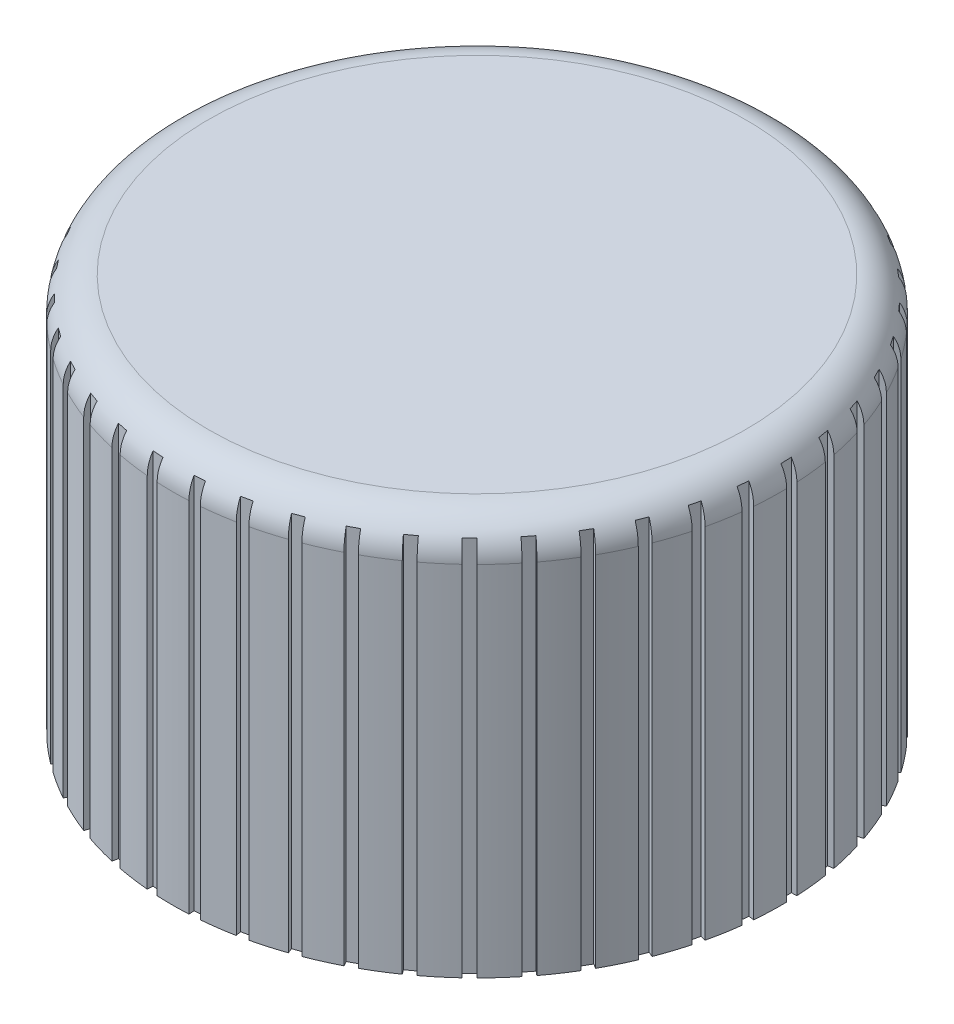
SolidWorks part; units mm, degrees
ref_plane "Front Plane" through (0, 0, 0) normal (0, 0, 1) x (1, 0, 0)
ref_plane "Top Plane" through (0, 0, 0) normal (0, 1, 0) x (1, 0, 0)
ref_plane "Right Plane" through (0, 0, 0) normal (1, 0, 0) x (0, 0, -1)
sketch "草图1" plane through (0, 0, 0) normal (0, 1, 0) x (1, 0, 0)
  circle A0 centre (0, 0) radius 8.5
extrude "凸台-拉伸1" add sketch "草图1" along normal blind 11
sketch "草图2" plane through (0, 0, 0) normal (0, -1, 0) x (1, 0, 0)
  circle A0 centre (0, 0) radius 2.95
extrude "切除-拉伸1" cut sketch "草图2" against normal blind 8.8
fillet "圆角1" radius 1 1 edges at (0, 11, 8.5)
sketch "草图3" plane through (0, 0, 0) normal (0, -1, 0) x (1, 0, 0)
  line L9 (4.7426, 1.5835) -> (6.5, 2.5981)
  line L10 (1, 4.899) -> (1, 6.9282)
  line L11 (-1, 4.899) -> (-1, 6.9282)
  line L12 (3.7426, 3.3155) -> (5.5, 4.3301)
  line L13 (3.7426, -3.3155) -> (5.5, -4.3301)
  line L14 (4.7426, -1.5835) -> (6.5, -2.5981)
  line L15 (-1, -4.899) -> (-1, -6.9282)
  line L16 (1, -4.899) -> (1, -6.9282)
  line L17 (-4.7426, -1.5835) -> (-6.5, -2.5981)
  line L18 (-3.7426, -3.3155) -> (-5.5, -4.3301)
  line L19 (-3.7426, 3.3155) -> (-5.5, 4.3301)
  line L20 (-4.7426, 1.5835) -> (-6.5, 2.5981)
  arc A0 (-4.7426, 1.5835) -> (-4.7426, -1.5835) centre (0, 0) ccw
  arc A11 (-6.5, 2.5981) -> (-6.5, -2.5981) centre (0, 0) ccw
  arc A12 (-3.7426, -3.3155) -> (-1, -4.899) centre (0, 0) ccw
  arc A13 (-5.5, -4.3301) -> (-1, -6.9282) centre (0, 0) ccw
  arc A14 (1, -4.899) -> (3.7426, -3.3155) centre (0, 0) ccw
  arc A15 (1, -6.9282) -> (5.5, -4.3301) centre (0, 0) ccw
  arc A16 (4.7426, -1.5835) -> (4.7426, 1.5835) centre (0, 0) ccw
  arc A17 (6.5, -2.5981) -> (6.5, 2.5981) centre (0, 0) ccw
  arc A18 (3.7426, 3.3155) -> (1, 4.899) centre (0, 0) ccw
  arc A19 (5.5, 4.3301) -> (1, 6.9282) centre (0, 0) ccw
  arc A20 (-1, 4.899) -> (-3.7426, 3.3155) centre (0, 0) ccw
  arc A21 (-1, 6.9282) -> (-5.5, 4.3301) centre (0, 0) ccw
  point P0 (1, 0)
  point P1 (0, 7)
  point P4 (1, 11.9)
  point P5 (-1, 0)
  point P8 (-1, 11.9)
  point P36 (0, 0)
  dimension "D1" = 6
extrude "切除-拉伸2" cut sketch "草图3" against normal blind 9
sketch "草图5" plane through (0, 11, 0) normal (0, 1, 0) x (1, 0, 0)
  line L2 (1.1615, 8.2645) -> (1.0132, 8.2854)
  line L3 (0, 8.3457) -> (-0.1498, 8.3457)
  line L4 (0, 8.3457) -> (0.1498, 8.3457)
  line L5 (-0.1498, 8.3457) -> (-0.1483, 8.4987)
  line L6 (0.1498, 8.3457) -> (0.1483, 8.4987)
  line L7 (1.1615, 8.2645) -> (1.3098, 8.2437)
  line L8 (1.0132, 8.2854) -> (1.0359, 8.4366)
  line L9 (1.3098, 8.2437) -> (1.3297, 8.3954)
  line L10 (2.3004, 8.0224) -> (2.1564, 8.0637)
  line L11 (2.3004, 8.0224) -> (2.4444, 7.9812)
  line L12 (2.1564, 8.0637) -> (2.2, 8.2104)
  line L13 (2.4444, 7.9812) -> (2.4852, 8.1286)
  line L14 (3.3945, 7.6242) -> (3.2577, 7.6851)
  line L15 (3.3945, 7.6242) -> (3.5313, 7.5633)
  line L16 (3.2577, 7.6851) -> (3.3212, 7.8243)
  line L17 (3.5313, 7.5633) -> (3.5923, 7.7036)
  line L18 (4.4226, 7.0776) -> (4.2956, 7.157)
  line L19 (4.4226, 7.0776) -> (4.5496, 6.9982)
  line L20 (4.2956, 7.157) -> (4.3778, 7.2859)
  line L21 (4.5496, 6.9982) -> (4.6294, 7.1287)
  line L22 (5.3645, 6.3932) -> (5.2498, 6.4895)
  line L23 (5.3645, 6.3932) -> (5.4793, 6.2969)
  line L24 (5.2498, 6.4895) -> (5.3492, 6.6057)
  line L25 (5.4793, 6.2969) -> (5.5765, 6.415)
  line L26 (6.2021, 5.5844) -> (6.1019, 5.6957)
  line L27 (6.2021, 5.5844) -> (6.3023, 5.4731)
  line L28 (6.1019, 5.6957) -> (6.2165, 5.797)
  line L29 (6.3023, 5.4731) -> (6.415, 5.5765)
  line L30 (6.9189, 4.6669) -> (6.8352, 4.791)
  line L31 (6.9189, 4.6669) -> (7.0027, 4.5427)
  line L32 (6.8352, 4.791) -> (6.9628, 4.8754)
  line L33 (7.0027, 4.5427) -> (7.1287, 4.6294)
  line L34 (7.5011, 3.6585) -> (7.4355, 3.7931)
  line L35 (7.5011, 3.6585) -> (7.5668, 3.5239)
  line L36 (7.4355, 3.7931) -> (7.5736, 3.8589)
  line L37 (7.5668, 3.5239) -> (7.7036, 3.5923)
  line L38 (7.9373, 2.579) -> (7.891, 2.7214)
  line L39 (7.9373, 2.579) -> (7.9836, 2.4365)
  line L40 (7.891, 2.7214) -> (8.0369, 2.7673)
  line L41 (7.9836, 2.4365) -> (8.1286, 2.4852)
  line L42 (8.219, 1.4492) -> (8.1929, 1.5967)
  line L43 (8.219, 1.4492) -> (8.245, 1.3017)
  line L44 (8.1929, 1.5967) -> (8.3438, 1.6219)
  line L45 (8.245, 1.3017) -> (8.3954, 1.3297)
  line L46 (8.3407, 0.2913) -> (8.3354, 0.4409)
  line L47 (8.3407, 0.2913) -> (8.3459, 0.1416)
  line L48 (8.3354, 0.4409) -> (8.4884, 0.4449)
  line L49 (8.3459, 0.1416) -> (8.4987, 0.1483)
  line L50 (8.3, -0.8724) -> (8.3157, -0.7234)
  line L51 (8.3, -0.8724) -> (8.2844, -1.0213)
  line L52 (8.3157, -0.7234) -> (8.4677, -0.7408)
  line L53 (8.2844, -1.0213) -> (8.4366, -1.0359)
  line L54 (8.0978, -2.019) -> (8.1341, -1.8737)
  line L55 (8.0978, -2.019) -> (8.0616, -2.1643)
  line L56 (8.1341, -1.8737) -> (8.2821, -1.9121)
  line L57 (8.0616, -2.1643) -> (8.2104, -2.2)
  line L58 (7.738, -3.1264) -> (7.7941, -2.9875)
  line L59 (7.738, -3.1264) -> (7.6819, -3.2652)
  line L60 (7.7941, -2.9875) -> (7.9354, -3.0461)
  line L61 (7.6819, -3.2652) -> (7.8243, -3.3212)
  line L62 (7.2276, -4.1729) -> (7.3025, -4.0432)
  line L63 (7.2276, -4.1729) -> (7.1527, -4.3026)
  line L64 (7.3025, -4.0432) -> (7.4343, -4.1209)
  line L65 (7.1527, -4.3026) -> (7.2859, -4.3778)
  line L66 (6.5765, -5.1382) -> (6.6687, -5.0201)
  line L67 (6.5765, -5.1382) -> (6.4843, -5.2562)
  line L68 (6.6687, -5.0201) -> (6.7884, -5.1154)
  line L69 (6.4843, -5.2562) -> (6.6057, -5.3492)
  line L70 (5.7974, -6.0034) -> (5.9052, -5.8994)
  line L71 (5.7974, -6.0034) -> (5.6897, -6.1075)
  line L72 (5.9052, -5.8994) -> (6.0104, -6.0104)
  line L73 (5.6897, -6.1075) -> (5.797, -6.2165)
  line L74 (4.9055, -6.7518) -> (5.0267, -6.6638)
  line L75 (4.9055, -6.7518) -> (4.7843, -6.8399)
  line L76 (5.0267, -6.6638) -> (5.1154, -6.7884)
  line L77 (4.7843, -6.8399) -> (4.8754, -6.9628)
  line L78 (3.9181, -7.3689) -> (4.0503, -7.2985)
  line L79 (3.9181, -7.3689) -> (3.7859, -7.4392)
  line L80 (4.0503, -7.2985) -> (4.1209, -7.4343)
  line L81 (3.7859, -7.4392) -> (3.8589, -7.5736)
  line L82 (2.8544, -7.8424) -> (2.9951, -7.7912)
  line L83 (2.8544, -7.8424) -> (2.7137, -7.8937)
  line L84 (2.9951, -7.7912) -> (3.0461, -7.9354)
  line L85 (2.7137, -7.8937) -> (2.7673, -8.0369)
  line L86 (1.7352, -8.1634) -> (1.8817, -8.1322)
  line L87 (1.7352, -8.1634) -> (1.5887, -8.1945)
  line L88 (1.8817, -8.1322) -> (1.9121, -8.2821)
  line L89 (1.5887, -8.1945) -> (1.6219, -8.3438)
  line L90 (0.5822, -8.3254) -> (0.7316, -8.315)
  line L91 (0.5822, -8.3254) -> (0.4328, -8.3359)
  line L92 (0.7316, -8.315) -> (0.7408, -8.4677)
  line L93 (0.4328, -8.3359) -> (0.4449, -8.4884)
  line L94 (-0.5822, -8.3254) -> (-0.4328, -8.3359)
  line L95 (-0.5822, -8.3254) -> (-0.7316, -8.315)
  line L96 (-0.4328, -8.3359) -> (-0.4449, -8.4884)
  line L97 (-0.7316, -8.315) -> (-0.7408, -8.4677)
  line L98 (-1.7352, -8.1634) -> (-1.5887, -8.1945)
  line L99 (-1.7352, -8.1634) -> (-1.8817, -8.1322)
  line L100 (-1.5887, -8.1945) -> (-1.6219, -8.3438)
  line L101 (-1.8817, -8.1322) -> (-1.9121, -8.2821)
  line L102 (-2.8544, -7.8424) -> (-2.7137, -7.8937)
  line L103 (-2.8544, -7.8424) -> (-2.9951, -7.7912)
  line L104 (-2.7137, -7.8937) -> (-2.7673, -8.0369)
  line L105 (-2.9951, -7.7912) -> (-3.0461, -7.9354)
  line L106 (-3.9181, -7.3689) -> (-3.7859, -7.4392)
  line L107 (-3.9181, -7.3689) -> (-4.0503, -7.2985)
  line L108 (-3.7859, -7.4392) -> (-3.8589, -7.5736)
  line L109 (-4.0503, -7.2985) -> (-4.1209, -7.4343)
  line L110 (-4.9055, -6.7518) -> (-4.7843, -6.8399)
  line L111 (-4.9055, -6.7518) -> (-5.0267, -6.6638)
  line L112 (-4.7843, -6.8399) -> (-4.8754, -6.9628)
  line L113 (-5.0267, -6.6638) -> (-5.1154, -6.7884)
  line L114 (-5.7974, -6.0034) -> (-5.6897, -6.1075)
  line L115 (-5.7974, -6.0034) -> (-5.9052, -5.8994)
  line L116 (-5.6897, -6.1075) -> (-5.797, -6.2165)
  line L117 (-5.9052, -5.8994) -> (-6.0104, -6.0104)
  line L118 (-6.5765, -5.1382) -> (-6.4843, -5.2562)
  line L119 (-6.5765, -5.1382) -> (-6.6687, -5.0201)
  line L120 (-6.4843, -5.2562) -> (-6.6057, -5.3492)
  line L121 (-6.6687, -5.0201) -> (-6.7884, -5.1154)
  line L122 (-7.2276, -4.1729) -> (-7.1527, -4.3026)
  line L123 (-7.2276, -4.1729) -> (-7.3025, -4.0432)
  line L124 (-7.1527, -4.3026) -> (-7.2859, -4.3778)
  line L125 (-7.3025, -4.0432) -> (-7.4343, -4.1209)
  line L126 (-7.738, -3.1264) -> (-7.6819, -3.2652)
  line L127 (-7.738, -3.1264) -> (-7.7941, -2.9875)
  line L128 (-7.6819, -3.2652) -> (-7.8243, -3.3212)
  line L129 (-7.7941, -2.9875) -> (-7.9354, -3.0461)
  line L130 (-8.0978, -2.019) -> (-8.0616, -2.1643)
  line L131 (-8.0978, -2.019) -> (-8.1341, -1.8737)
  line L132 (-8.0616, -2.1643) -> (-8.2104, -2.2)
  line L133 (-8.1341, -1.8737) -> (-8.2821, -1.9121)
  line L134 (-8.3, -0.8724) -> (-8.2844, -1.0213)
  line L135 (-8.3, -0.8724) -> (-8.3157, -0.7234)
  line L136 (-8.2844, -1.0213) -> (-8.4366, -1.0359)
  line L137 (-8.3157, -0.7234) -> (-8.4677, -0.7408)
  line L138 (-8.3407, 0.2913) -> (-8.3459, 0.1416)
  line L139 (-8.3407, 0.2913) -> (-8.3354, 0.4409)
  line L140 (-8.3459, 0.1416) -> (-8.4987, 0.1483)
  line L141 (-8.3354, 0.4409) -> (-8.4884, 0.4449)
  line L142 (-8.219, 1.4492) -> (-8.245, 1.3017)
  line L143 (-8.219, 1.4492) -> (-8.1929, 1.5967)
  line L144 (-8.245, 1.3017) -> (-8.3954, 1.3297)
  line L145 (-8.1929, 1.5967) -> (-8.3438, 1.6219)
  line L146 (-7.9373, 2.579) -> (-7.9836, 2.4365)
  line L147 (-7.9373, 2.579) -> (-7.891, 2.7214)
  line L148 (-7.9836, 2.4365) -> (-8.1286, 2.4852)
  line L149 (-7.891, 2.7214) -> (-8.0369, 2.7673)
  line L150 (-7.5011, 3.6585) -> (-7.5668, 3.5239)
  line L151 (-7.5011, 3.6585) -> (-7.4355, 3.7931)
  line L152 (-7.5668, 3.5239) -> (-7.7036, 3.5923)
  line L153 (-7.4355, 3.7931) -> (-7.5736, 3.8589)
  line L154 (-6.9189, 4.6669) -> (-7.0027, 4.5427)
  line L155 (-6.9189, 4.6669) -> (-6.8352, 4.791)
  line L156 (-7.0027, 4.5427) -> (-7.1287, 4.6294)
  line L157 (-6.8352, 4.791) -> (-6.9628, 4.8754)
  line L158 (-6.2021, 5.5844) -> (-6.3023, 5.4731)
  line L159 (-6.2021, 5.5844) -> (-6.1019, 5.6957)
  line L160 (-6.3023, 5.4731) -> (-6.415, 5.5765)
  line L161 (-6.1019, 5.6957) -> (-6.2165, 5.797)
  line L162 (-5.3645, 6.3932) -> (-5.4793, 6.2969)
  line L163 (-5.3645, 6.3932) -> (-5.2498, 6.4895)
  line L164 (-5.4793, 6.2969) -> (-5.5765, 6.415)
  line L165 (-5.2498, 6.4895) -> (-5.3492, 6.6057)
  line L166 (-4.4226, 7.0776) -> (-4.5496, 6.9982)
  line L167 (-4.4226, 7.0776) -> (-4.2956, 7.157)
  line L168 (-4.5496, 6.9982) -> (-4.6294, 7.1287)
  line L169 (-4.2956, 7.157) -> (-4.3778, 7.2859)
  line L170 (-3.3945, 7.6242) -> (-3.5313, 7.5633)
  line L171 (-3.3945, 7.6242) -> (-3.2577, 7.6851)
  line L172 (-3.5313, 7.5633) -> (-3.5923, 7.7036)
  line L173 (-3.2577, 7.6851) -> (-3.3212, 7.8243)
  line L174 (-2.3004, 8.0224) -> (-2.4444, 7.9812)
  line L175 (-2.3004, 8.0224) -> (-2.1564, 8.0637)
  line L176 (-2.4444, 7.9812) -> (-2.4852, 8.1286)
  line L177 (-2.1564, 8.0637) -> (-2.2, 8.2104)
  line L178 (-1.1615, 8.2645) -> (-1.3098, 8.2437)
  line L179 (-1.1615, 8.2645) -> (-1.0132, 8.2854)
  line L180 (-1.3098, 8.2437) -> (-1.3297, 8.3954)
  line L181 (-1.0132, 8.2854) -> (-1.0359, 8.4366)
  circle A0 centre (0, 0) radius 8.5 construction
  arc A1 (0.1483, 8.4987) -> (-0.1483, 8.4987) centre (0, 0) ccw
  arc A2 (1.3297, 8.3954) -> (1.0359, 8.4366) centre (0, 0) ccw
  arc A3 (2.4852, 8.1286) -> (2.2, 8.2104) centre (0, 0) ccw
  arc A4 (3.5923, 7.7036) -> (3.3212, 7.8243) centre (0, 0) ccw
  arc A5 (4.6294, 7.1287) -> (4.3778, 7.2859) centre (0, 0) ccw
  arc A6 (5.5765, 6.415) -> (5.3492, 6.6057) centre (0, 0) ccw
  arc A7 (6.415, 5.5765) -> (6.2165, 5.797) centre (0, 0) ccw
  arc A8 (7.1287, 4.6294) -> (6.9628, 4.8754) centre (0, 0) ccw
  arc A9 (7.7036, 3.5923) -> (7.5736, 3.8589) centre (0, 0) ccw
  arc A10 (8.1286, 2.4852) -> (8.0369, 2.7673) centre (0, 0) ccw
  arc A11 (8.3954, 1.3297) -> (8.3438, 1.6219) centre (0, 0) ccw
  arc A12 (8.4987, 0.1483) -> (8.4884, 0.4449) centre (0, 0) ccw
  arc A13 (8.4366, -1.0359) -> (8.4677, -0.7408) centre (0, 0) ccw
  arc A14 (8.2104, -2.2) -> (8.2821, -1.9121) centre (0, 0) ccw
  arc A15 (7.8243, -3.3212) -> (7.9354, -3.0461) centre (0, 0) ccw
  arc A16 (7.2859, -4.3778) -> (7.4343, -4.1209) centre (0, 0) ccw
  arc A17 (6.6057, -5.3492) -> (6.7884, -5.1154) centre (0, 0) ccw
  arc A18 (5.797, -6.2165) -> (6.0104, -6.0104) centre (0, 0) ccw
  arc A19 (4.8754, -6.9628) -> (5.1154, -6.7884) centre (0, 0) ccw
  arc A20 (3.8589, -7.5736) -> (4.1209, -7.4343) centre (0, 0) ccw
  arc A21 (2.7673, -8.0369) -> (3.0461, -7.9354) centre (0, 0) ccw
  arc A22 (1.6219, -8.3438) -> (1.9121, -8.2821) centre (0, 0) ccw
  arc A23 (0.4449, -8.4884) -> (0.7408, -8.4677) centre (0, 0) ccw
  arc A24 (-0.7408, -8.4677) -> (-0.4449, -8.4884) centre (0, 0) ccw
  arc A25 (-1.9121, -8.2821) -> (-1.6219, -8.3438) centre (0, 0) ccw
  arc A26 (-3.0461, -7.9354) -> (-2.7673, -8.0369) centre (0, 0) ccw
  arc A27 (-4.1209, -7.4343) -> (-3.8589, -7.5736) centre (0, 0) ccw
  arc A28 (-5.1154, -6.7884) -> (-4.8754, -6.9628) centre (0, 0) ccw
  arc A29 (-6.0104, -6.0104) -> (-5.797, -6.2165) centre (0, 0) ccw
  arc A30 (-6.7884, -5.1154) -> (-6.6057, -5.3492) centre (0, 0) ccw
  arc A31 (-7.4343, -4.1209) -> (-7.2859, -4.3778) centre (0, 0) ccw
  arc A32 (-7.9354, -3.0461) -> (-7.8243, -3.3212) centre (0, 0) ccw
  arc A33 (-8.2821, -1.9121) -> (-8.2104, -2.2) centre (0, 0) ccw
  arc A34 (-8.4677, -0.7408) -> (-8.4366, -1.0359) centre (0, 0) ccw
  arc A35 (-8.4884, 0.4449) -> (-8.4987, 0.1483) centre (0, 0) ccw
  arc A36 (-8.3438, 1.6219) -> (-8.3954, 1.3297) centre (0, 0) ccw
  arc A37 (-8.0369, 2.7673) -> (-8.1286, 2.4852) centre (0, 0) ccw
  arc A38 (-7.5736, 3.8589) -> (-7.7036, 3.5923) centre (0, 0) ccw
  arc A39 (-6.9628, 4.8754) -> (-7.1287, 4.6294) centre (0, 0) ccw
  arc A40 (-6.2165, 5.797) -> (-6.415, 5.5765) centre (0, 0) ccw
  arc A41 (-5.3492, 6.6057) -> (-5.5765, 6.415) centre (0, 0) ccw
  arc A42 (-4.3778, 7.2859) -> (-4.6294, 7.1287) centre (0, 0) ccw
  arc A43 (-3.3212, 7.8243) -> (-3.5923, 7.7036) centre (0, 0) ccw
  arc A44 (-2.2, 8.2104) -> (-2.4852, 8.1286) centre (0, 0) ccw
  arc A45 (-1.0359, 8.4366) -> (-1.3297, 8.3954) centre (0, 0) ccw
  point P0 (0, 8.3457)
  dimension "D1" = 45
extrude "切除-拉伸3" cut sketch "草图5" against normal through all
